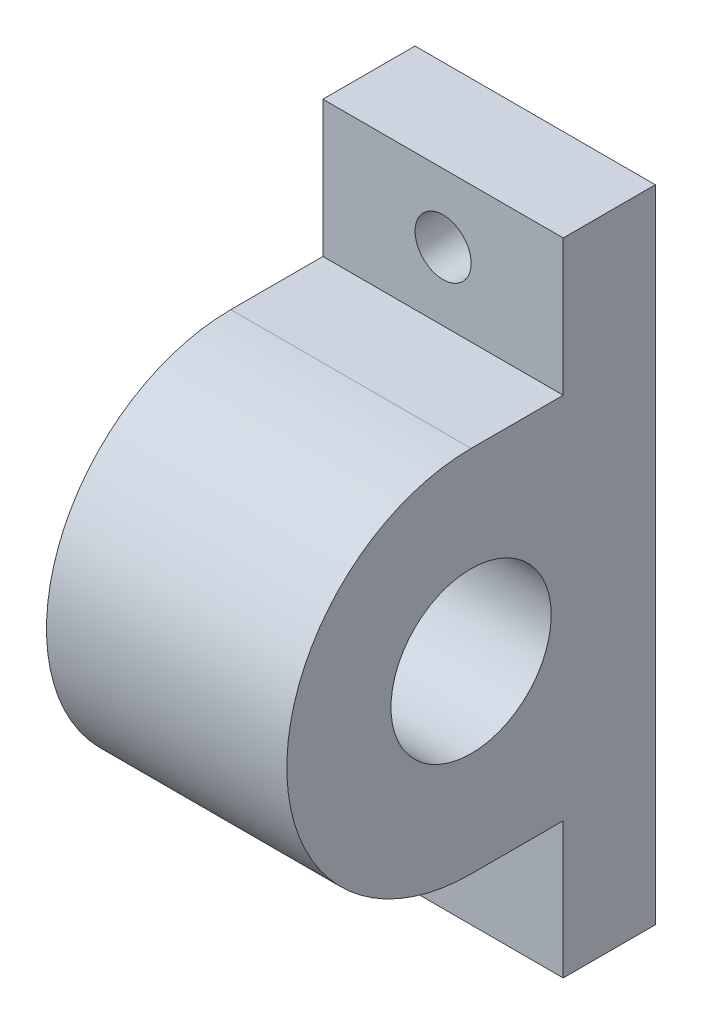
SolidWorks part; units mm, degrees
ref_plane "Front Plane" through (0, 0, 0) normal (0, 0, 1) x (1, 0, 0)
ref_plane "Top Plane" through (0, 0, 0) normal (0, 1, 0) x (1, 0, 0)
ref_plane "Right Plane" through (0, 0, 0) normal (1, 0, 0) x (0, 0, -1)
sketch "Sketch1" plane through (0, 0, 0) normal (0, 0, 1) x (1, 0, 0)
  line L1 (235.8812, -204.6746) -> (250.8812, -204.6746)
  line L2 (235.8812, -204.6746) -> (235.8812, -164.6746)
  line L3 (235.8812, -164.6746) -> (250.8812, -164.6746)
  line L4 (250.8812, -204.6746) -> (250.8812, -164.6746)
  dimension "D1" = 15
  dimension "D2" = 40
extrude "Boss-Extrude1" add sketch "Sketch1" along normal blind 23
sketch "Sketch2" plane through (250.8812, 0, 0) normal (1, 0, 0) x (0, 0, -1)
  line L0 (-23, -204.6746) -> (-23, -164.6746) construction
  line L1 (0, -229.3861) -> (0, 60.6139) construction
  line L2 (-53.9362, -184.6746) -> (5.9362, -184.6746) construction
  line L3 (-11.5, -173.1746) -> (0, -173.1746) construction
  line L4 (0, -204.6746) -> (0, -164.6746) construction
  line L5 (-5.75, -173.1746) -> (-5.75, -164.6746) construction
  line L6 (-23, -164.6746) -> (0, -164.6746) construction
  line L7 (-11.5, -173.1746) -> (-5.75, -173.1746)
  line L8 (-5.75, -173.1746) -> (-5.75, -164.6746)
  line L9 (-5.75, -164.6746) -> (0, -164.6746)
  line L10 (0, -164.6746) -> (0, -204.6746)
  line L11 (-11.5, -196.1746) -> (-5.75, -196.1746)
  line L12 (-5.75, -196.1746) -> (-5.75, -204.6746)
  line L13 (-5.75, -204.6746) -> (0, -204.6746)
  circle A0 centre (-11.5, -184.6746) radius 11.5 construction
  arc A1 (-11.5, -173.1746) -> (-11.5, -196.1746) centre (-11.5, -184.6746) ccw
  point P25 (0, -184.6746)
extrude "Cut-Extrude1" cut sketch "Sketch2" against normal through all flip side to cut
sketch "Sketch3" plane through (250.8812, 0, 0) normal (1, 0, 0) x (0, 0, -1)
  circle A0 centre (-11.5, -184.6746) radius 11.5 construction
  circle A1 centre (-11.5, -184.6746) radius 5
  dimension "D1" = 10
extrude "Cut-Extrude2" cut sketch "Sketch3" against normal through all
sketch "Sketch4" plane through (0, 0, 5.75) normal (0, 0, 1) x (1, 0, 0)
  line L0 (235.8812, -164.6746) -> (250.8812, -173.1746) construction
  line L1 (250.8812, -164.6746) -> (250.8812, -173.1746) construction
  line L2 (250.8812, -164.6746) -> (235.8812, -173.1746) construction
  line L3 (235.8812, -164.6746) -> (235.8812, -173.1746) construction
  line L4 (235.8812, -196.1746) -> (250.8812, -204.6746) construction
  line L5 (235.8812, -204.6746) -> (250.8812, -204.6746) construction
  line L6 (235.8812, -204.6746) -> (250.8812, -196.1746) construction
  circle A0 centre (243.3812, -200.4246) radius 1.75
  circle A1 centre (243.3812, -168.9246) radius 1.75
  point P23 (0, 0)
  point P24 (243.3812, -168.9246)
  point P25 (0, 0)
  point P26 (243.3812, -200.4246)
  point P27 (0, 0)
  point P29 (0, 0)
  point P31 (0, 0)
  dimension "D1" = 3.5
  dimension "D2" = 3.5
extrude "Cut-Extrude3" cut sketch "Sketch4" against normal blind 17
